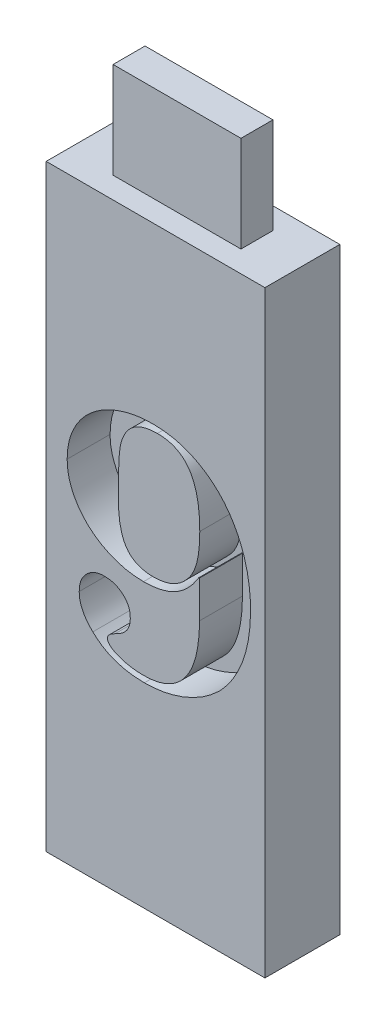
SolidWorks part; units mm, degrees
ref_plane "Front Plane" through (0, 0, 0) normal (0, 0, 1) x (1, 0, 0)
ref_plane "Top Plane" through (0, 0, 0) normal (0, 1, 0) x (1, 0, 0)
ref_plane "Right Plane" through (0, 0, 0) normal (1, 0, 0) x (0, 0, -1)
sketch "Sketch1" plane through (0, 0, 0) normal (0, 0, 1) x (1, 0, 0)
  line L1 (-8.69, -23.749) -> (8.69, -23.749)
  line L2 (-8.69, -23.749) -> (-8.69, 23.749)
  line L3 (-8.69, 23.749) -> (8.69, 23.749)
  line L4 (8.69, -23.749) -> (8.69, 23.749)
  line L5 (-8.69, -23.749) -> (8.69, 23.749) construction
  line L6 (-8.69, 23.749) -> (8.69, -23.749) construction
  point P0 (0, 0)
  dimension "D1" = 17.38
  dimension "D2" = 47.498
extrude "Boss-Extrude1" add sketch "Sketch1" along normal blind 5.95
sketch "Sketch2" plane through (0, 0, 5.95) normal (0, 0, 1) x (1, 0, 0)
  line L0 (0, 23.749) -> (0, -23.749) construction
  line L1 (8.69, 23.749) -> (-8.69, 23.749) construction
  line L2 (-8.69, -23.749) -> (8.69, -23.749) construction
  line L3 (0, -23.749) -> (0, 0) construction
  line L4 (0, 0) -> (-8.69, 0) construction
  line L5 (-8.69, 23.749) -> (-8.69, -23.749) construction
  line L6 (-8.69, 0) -> (8.69, 0) construction
  line L7 (8.69, -23.749) -> (8.69, 23.749) construction
  line L8 (-8.69, -23.749) -> (8.69, -23.749) construction
  line L9 (-8.69, -21.209) -> (8.69, -21.209) construction
  line L10 (-8.69, -18.669) -> (8.69, -18.669) construction
  line L11 (-8.69, -16.129) -> (8.69, -16.129) construction
  line L12 (-8.69, -13.589) -> (8.69, -13.589) construction
  line L13 (-8.69, -11.049) -> (8.69, -11.049) construction
  line L14 (-8.69, -8.509) -> (8.69, -8.509) construction
  line L15 (-8.69, -5.969) -> (8.69, -5.969) construction
  line L16 (-8.69, -3.429) -> (8.69, -3.429) construction
  line L17 (-8.69, -0.889) -> (8.69, -0.889) construction
  line L18 (-8.69, 1.651) -> (8.69, 1.651) construction
  line L19 (-8.69, 4.191) -> (8.69, 4.191) construction
  line L20 (-8.69, 6.731) -> (8.69, 6.731) construction
  line L21 (-8.69, 9.271) -> (8.69, 9.271) construction
  line L22 (-8.69, 11.811) -> (8.69, 11.811) construction
  line L23 (-8.69, 14.351) -> (8.69, 14.351) construction
  line L24 (-8.69, 16.891) -> (8.69, 16.891) construction
  line L25 (-8.69, 19.431) -> (8.69, 19.431) construction
  line L26 (-8.69, 21.971) -> (8.69, 21.971) construction
  line L27 (-8.69, 23.749) -> (-8.69, -23.749) construction
  line L28 (-6.15, 23.749) -> (-6.15, -23.749) construction
  line L29 (-3.61, 23.749) -> (-3.61, -23.749) construction
  line L30 (-1.07, 23.749) -> (-1.07, -23.749) construction
  line L31 (1.47, 23.749) -> (1.47, -23.749) construction
  line L32 (4.01, 23.749) -> (4.01, -23.749) construction
  line L33 (6.55, 23.749) -> (6.55, -23.749) construction
  text T0 "9\r\n" font "Engravers MT" height in points 72
  dimension "D1" = 19
  dimension "D2" = 2.54
  dimension "D4" = 2.54
  dimension "D3" = 7
extrude "Cut-Extrude1" cut sketch "Sketch2" against normal blind 3.41
sketch "Sketch3" plane through (0, 23.749, 0) normal (0, 1, 0) x (1, 0, 0)
  line L0 (0, 0) -> (0, -5.95) construction
  line L1 (8.69, -5.95) -> (-8.69, -5.95) construction
  line L2 (0, -5.95) -> (0, -2.975) construction
  line L3 (0, -2.975) -> (-8.69, -2.975) construction
  line L4 (-8.69, -5.95) -> (-8.69, 0) construction
  line L5 (-8.69, -2.975) -> (8.69, -2.975) construction
  line L6 (8.69, -5.95) -> (8.69, 0) construction
  line L8 (-5.08, -4.245) -> (5.08, -4.245)
  line L9 (-5.08, -4.245) -> (-5.08, -1.705)
  line L10 (-5.08, -1.705) -> (5.08, -1.705)
  line L11 (5.08, -4.245) -> (5.08, -1.705)
  line L12 (-5.08, -4.245) -> (5.08, -1.705) construction
  line L13 (-5.08, -1.705) -> (5.08, -4.245) construction
  dimension "D1" = 2.54
  dimension "D2" = 10.16
extrude "Boss-Extrude2" add sketch "Sketch3" along normal blind 7.62
